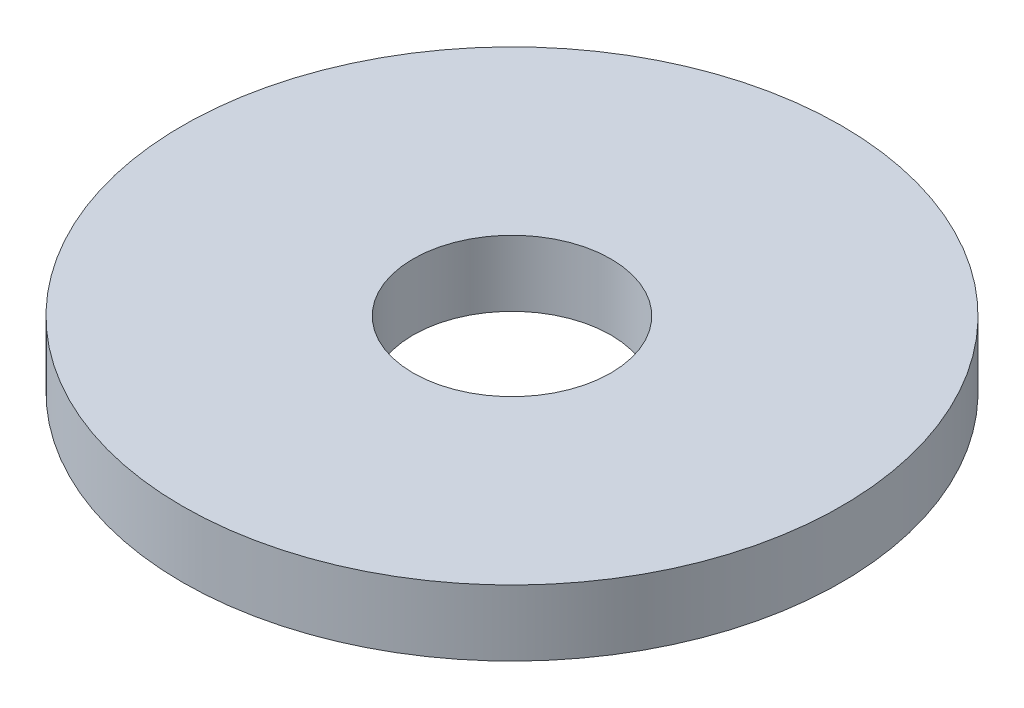
SolidWorks part; units mm, degrees
ref_plane "Front Plane" through (0, 0, 0) normal (0, 0, 1) x (1, 0, 0)
ref_plane "Top Plane" through (0, 0, 0) normal (0, 1, 0) x (1, 0, 0)
ref_plane "Right Plane" through (0, 0, 0) normal (1, 0, 0) x (0, 0, -1)
sketch "Sketch2" plane through (0, 0, 0) normal (0, 1, 0) x (1, 0, 0)
  circle A0 centre (0, 0) radius 5
extrude "Boss-Extrude1" add sketch "Sketch2" along normal blind 1 contours A0
sketch "Sketch3" plane through (0, 1, 0) normal (0, 1, 0) x (1, 0, 0)
  circle A0 centre (0, 0) radius 1.5
extrude "Cut-Extrude1" cut sketch "Sketch3" against normal blind 1
